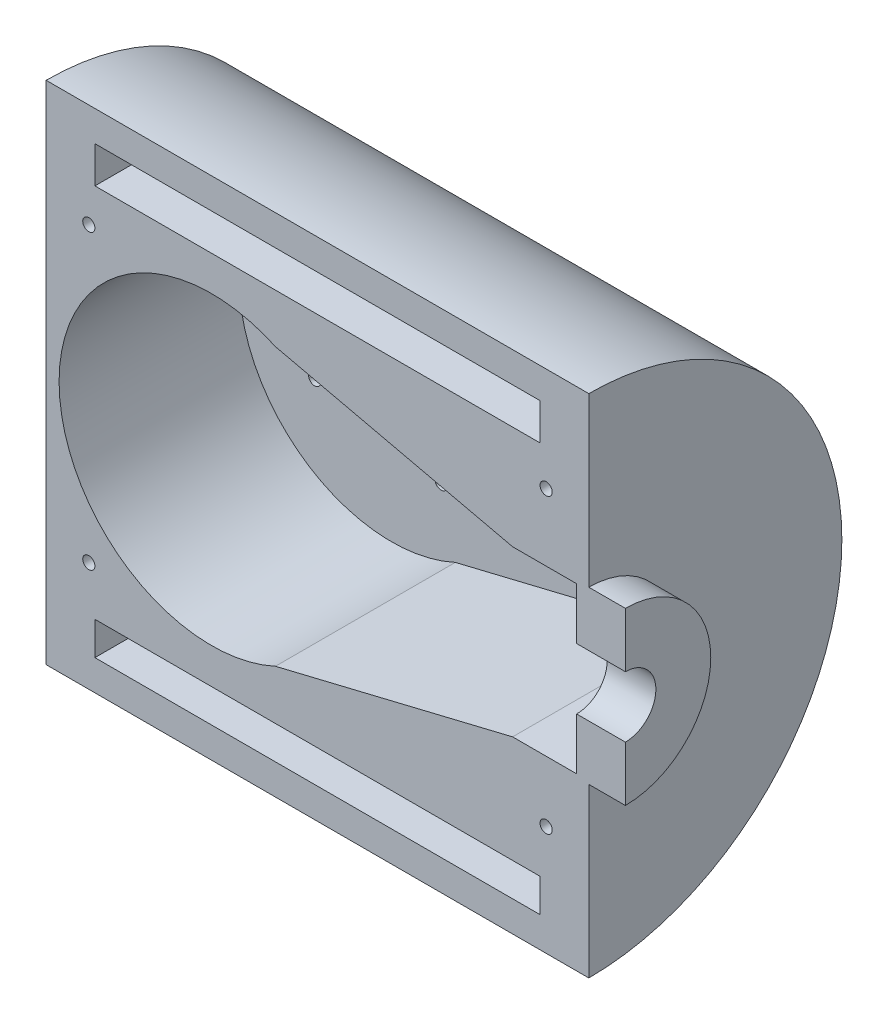
SolidWorks part; units mm, degrees
ref_plane "Front Plane" through (0, 0, 0) normal (0, 0, 1) x (1, 0, 0)
ref_plane "Top Plane" through (0, 0, 0) normal (0, 1, 0) x (1, 0, 0)
ref_plane "Right Plane" through (0, 0, 0) normal (1, 0, 0) x (0, 0, -1)
sketch "Sketch1" plane through (89.9437, 0, 0) normal (1, 0, 0) x (0, 0, -1)
  line L0 (-104.0163, 83.836) -> (-104.0163, 0.836)
  arc A0 (-104.0163, 0.836) -> (-104.0163, 83.836) centre (-104.0163, 42.336) ccw
  dimension "D1" = 83
extrude "Boss-Extrude2" add sketch "Sketch1" against normal blind 87
sketch "Sketch2" plane through (0, 0, 104.0163) normal (0, 0, 1) x (1, 0, 0)
  line L0 (89.9437, 55.836) -> (79.4451, 55.836)
  line L1 (89.9437, 83.836) -> (89.9437, 0.836) construction
  line L2 (79.4451, 55.836) -> (40.5513, 64.8055)
  line L3 (89.9437, 55.836) -> (89.9437, 28.836)
  line L4 (79.4451, 28.836) -> (40.5513, 19.4144)
  line L7 (89.9437, 28.836) -> (79.4451, 28.836)
  arc A0 (40.5513, 64.8055) -> (40.5513, 19.4144) centre (30.0675, 42.1099) ccw construction
  arc A1 (40.5513, 64.8055) -> (40.5513, 19.4144) centre (30.0675, 42.1099) ccw
extrude "Cut-Extrude1" cut sketch "Sketch2" against normal up to vertex (29.5 mm away)
ref_plane "Plane1" through (0, 0, 62.5163) normal (0, 0, -1) x (-1, 0, 0)
sketch "Sketch3" plane through (0, 0, 62.5163) normal (0, 0, -1) x (-1, 0, 0)
  circle A0 centre (-61.0675, 42.1099) radius 4.5
  circle A1 centre (-42.6574, 50.2643) radius 1 construction
  circle A2 centre (-42.6574, 50.2643) radius 1
  circle A3 centre (-21.9131, 54.6999) radius 1 construction
  circle A4 centre (-21.9131, 54.6999) radius 1
  circle A5 centre (-38.2218, 29.52) radius 1 construction
  circle A6 centre (-38.2218, 29.52) radius 1
  circle A7 centre (-17.4775, 33.9556) radius 1 construction
  circle A8 centre (-17.4775, 33.9556) radius 1
  dimension "D1" = 9
extrude "Cut-Extrude2" cut sketch "Sketch3" against normal through all
sketch "Sketch4" plane through (0, 0, 62.5163) normal (0, 0, -1) x (-1, 0, 0)
  circle A0 centre (-61.0675, 42.1099) radius 14.5
  circle A1 centre (-42.6574, 50.2643) radius 1.7 construction
  circle A2 centre (-42.6574, 50.2643) radius 1.7
  circle A3 centre (-21.9131, 54.6999) radius 1.7 construction
  circle A4 centre (-21.9131, 54.6999) radius 1.7
  circle A5 centre (-38.2218, 29.52) radius 1.7 construction
  circle A6 centre (-38.2218, 29.52) radius 1.7
  circle A7 centre (-17.4775, 33.9556) radius 1.7 construction
  circle A8 centre (-17.4775, 33.9556) radius 1.7
  dimension "D1" = 29
extrude "Cut-Extrude3" cut sketch "Sketch4" against normal blind 10
sketch "Sketch5" plane through (89.9437, 0, 0) normal (1, 0, 0) x (0, 0, -1)
  line L0 (-104.0163, 55.836) -> (-104.0163, 47.336)
  line L1 (-104.0163, 28.836) -> (-104.0163, 37.336)
  line L5 (-104.0163, 55.836) -> (-74.5163, 55.836)
  line L6 (-74.5163, 55.836) -> (-74.5163, 28.836)
  line L7 (-74.5163, 28.836) -> (-104.0163, 28.836)
  line L8 (-104.0163, 28.836) -> (-104.0163, 0.836)
  line L9 (-104.0163, 83.836) -> (-104.0163, 55.836)
  line L13 (-104.0163, 28.836) -> (-104.0163, 0.836)
  line L14 (-104.0163, 83.836) -> (-104.0163, 55.836)
  arc A0 (-104.0163, 37.336) -> (-104.0163, 47.336) centre (-104.0163, 42.336) ccw
  arc A1 (-104.0163, 0.836) -> (-104.0163, 83.836) centre (-104.0163, 42.336) ccw
  arc A2 (-104.0163, 0.836) -> (-104.0163, 83.836) centre (-104.0163, 42.336) ccw
  dimension "D1" = 0
extrude "Boss-Extrude3" add sketch "Sketch5" along normal blind 2
sketch "Sketch6" plane through (91.9437, 0, 0) normal (1, 0, 0) x (0, 0, -1)
  line L0 (-104.0163, 56.336) -> (-104.0163, 47.336)
  line L1 (-104.0163, 28.336) -> (-104.0163, 37.336)
  arc A0 (-104.0163, 28.336) -> (-104.0163, 56.336) centre (-104.0163, 42.336) ccw
  arc A1 (-104.0163, 37.336) -> (-104.0163, 47.336) centre (-104.0163, 42.336) ccw
  dimension "D1" = 14
extrude "Boss-Extrude4" add sketch "Sketch6" along normal blind 6
sketch "Sketch7" plane through (0, 0, 104.0163) normal (0, 0, 1) x (1, 0, 0)
  line L0 (2.9437, 0.836) -> (91.9437, 0.836) construction
  line L1 (10.9437, 78.836) -> (83.9437, 78.836)
  line L2 (10.9437, 78.836) -> (10.9437, 72.836)
  line L3 (10.9437, 72.836) -> (83.9437, 72.836)
  line L4 (83.9437, 78.836) -> (83.9437, 72.836)
  line L5 (10.9437, 11.2828) -> (83.9437, 11.2828)
  line L6 (10.9437, 11.2828) -> (10.9437, 5.836)
  line L7 (10.9437, 5.836) -> (83.9437, 5.836)
  line L8 (83.9437, 11.2828) -> (83.9437, 5.836)
  line L9 (2.9437, 83.836) -> (91.9437, 83.836) construction
  line L10 (10.9437, 72.836) -> (2.9437, 72.836) construction
  line L11 (2.9437, 83.836) -> (2.9437, 0.836) construction
  line L12 (83.9437, 72.836) -> (91.9437, 72.836) construction
  line L13 (91.9437, 83.836) -> (91.9437, 56.336) construction
  dimension "D1" = 5
  dimension "D2" = 5
  dimension "D3" = 6
  dimension "D4" = 8
extrude "Cut-Extrude4" cut sketch "Sketch7" against normal blind 7
sketch "Sketch8" plane through (0, 0, 62.5163) normal (0, 0, -1) x (-1, 0, 0)
  line L0 (-2.9437, 0.836) -> (-91.9437, 0.836) construction
  line L1 (-2.9437, 83.836) -> (-91.9437, 83.836) construction
  line L2 (-91.9437, 83.836) -> (-91.9437, 0.836) construction
  line L3 (-2.9437, 0.836) -> (-2.9437, 83.836) construction
  circle A0 centre (-84.9437, 66.836) radius 1
  circle A1 centre (-84.9437, 18.836) radius 1
  circle A2 centre (-9.9437, 66.836) radius 1
  circle A3 centre (-9.9437, 18.836) radius 1
  point P10 (0, 0)
  point P11 (0, 0)
  point P14 (0, 0)
  point P17 (0, 0)
  dimension "D1" = 2
  dimension "D2" = 18
  dimension "D3" = 17
  dimension "D4" = 7
  dimension "D5" = 7
extrude "Cut-Extrude5" cut sketch "Sketch8" against normal through all
sketch "Sketch9" plane through (0, 0, 62.5163) normal (0, 0, -1) x (-1, 0, 0)
  circle A0 centre (-84.9437, 66.836) radius 2.5
  circle A1 centre (-84.9437, 18.836) radius 2.5
  circle A2 centre (-9.9437, 66.836) radius 2.5
  circle A3 centre (-9.9437, 18.836) radius 2.5
  dimension "D1" = 5
extrude "Cut-Extrude6" cut sketch "Sketch9" against normal blind 32
